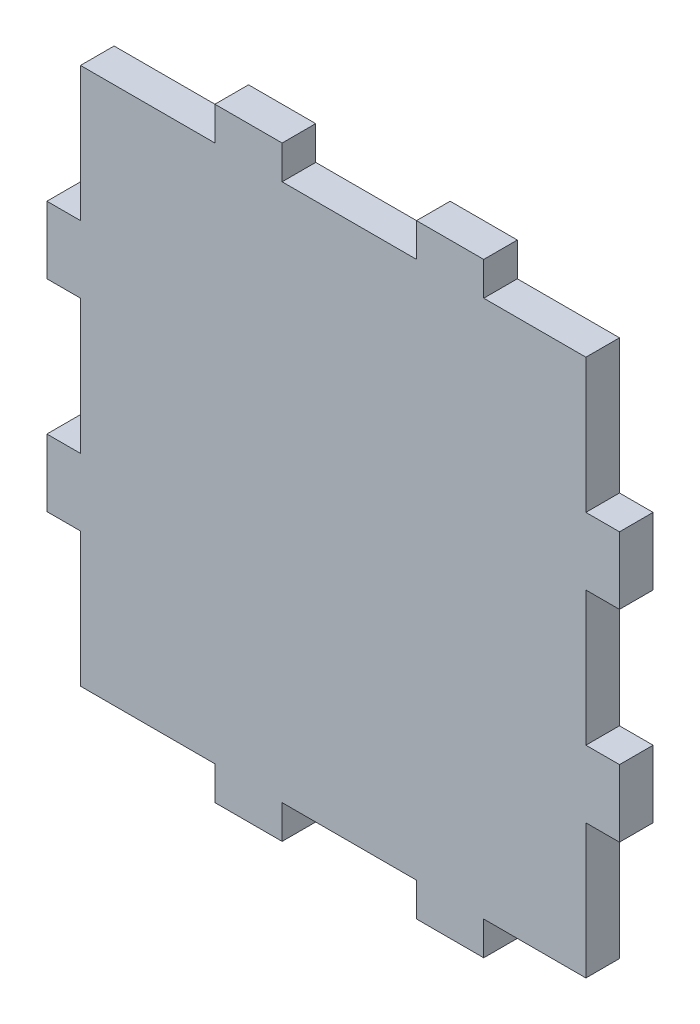
SolidWorks part; units mm, degrees
ref_plane "Front Plane" through (0, 0, 0) normal (0, 0, 1) x (1, 0, 0)
ref_plane "Top Plane" through (0, 0, 0) normal (0, 1, 0) x (1, 0, 0)
ref_plane "Right Plane" through (0, 0, 0) normal (1, 0, 0) x (0, 0, -1)
sketch "Sketch1" plane through (0, 0, 0) normal (0, 0, 1) x (1, 0, 0)
  line L0 (19.05, 0) -> (31.75, 0)
  line L1 (0, 0) -> (12.7, 0)
  line L2 (0, 0) -> (0, -12.7)
  line L3 (0, -50.8) -> (12.7, -50.8)
  line L4 (47.752, -19.05) -> (47.752, -31.75)
  line L6 (12.7, 0) -> (12.7, 3.175)
  line L7 (12.7, 3.175) -> (19.05, 3.175)
  line L8 (19.05, 0) -> (19.05, 3.175)
  line L9 (0, -19.05) -> (0, -31.75)
  line L10 (31.75, 0) -> (31.75, 3.175)
  line L11 (31.75, 3.175) -> (38.1, 3.175)
  line L12 (38.1, 0) -> (38.1, 3.175)
  line L13 (47.752, -12.7) -> (50.927, -12.7)
  line L14 (47.752, -38.1) -> (47.752, -50.8)
  line L15 (47.752, -19.05) -> (50.927, -19.05)
  line L16 (50.927, -12.7) -> (50.927, -19.05)
  line L17 (47.752, -31.75) -> (50.927, -31.75)
  line L18 (38.1, -50.8) -> (47.752, -50.8)
  line L19 (47.752, -38.1) -> (50.927, -38.1)
  line L20 (50.927, -31.75) -> (50.927, -38.1)
  line L21 (19.05, -50.8) -> (31.75, -50.8)
  line L22 (31.75, -50.8) -> (31.75, -53.975)
  line L23 (31.75, -53.975) -> (38.1, -53.975)
  line L24 (38.1, -50.8) -> (38.1, -53.975)
  line L25 (0, -38.1) -> (0, -50.8)
  line L26 (12.7, -50.8) -> (12.7, -53.975)
  line L27 (12.7, -53.975) -> (19.05, -53.975)
  line L28 (19.05, -50.8) -> (19.05, -53.975)
  line L29 (0, -38.1) -> (-3.175, -38.1)
  line L30 (38.1, 0) -> (47.752, 0)
  line L31 (0, -31.75) -> (-3.175, -31.75)
  line L32 (-3.175, -38.1) -> (-3.175, -31.75)
  line L33 (0, -19.05) -> (-3.175, -19.05)
  line L34 (47.752, 0) -> (47.752, -12.7)
  line L35 (0, -12.7) -> (-3.175, -12.7)
  line L36 (-3.175, -19.05) -> (-3.175, -12.7)
  dimension "D3" = 12.7
  dimension "D4" = 6.35
  dimension "D5" = 3.175
  dimension "D6" = 6.35
  dimension "D7" = 3.175
  dimension "D8" = 12.7
  dimension "D9" = 3.175
  dimension "D10" = 6.35
  dimension "D11" = 3.175
  dimension "D12" = 3.175
  dimension "D13" = 6.35
  dimension "D14" = 12.7
  dimension "D15" = 6.35
  dimension "D16" = 3.175
  dimension "D17" = 9.652
  dimension "D18" = 6.35
  dimension "D19" = 12.7
  dimension "D20" = 3.175
  dimension "D21" = 3.175
  dimension "D22" = 6.35
  dimension "D23" = 12.7
  dimension "D24" = 12.7
  dimension "D25" = 6.35
  dimension "D26" = 12.7
  dimension "D27" = 3.175
  dimension "D28" = 12.7
  dimension "D29" = 12.7
  dimension "D30" = 12.7
extrude "Boss-Extrude1" add sketch "Sketch1" along normal blind 3.175 contours L36 L33 L2 L31 L32 L29 L3 L26 L27 L28 L22 L23 L24 L4 L19 L20 L17 L15 L16 L13 L1 L12 L11 L10 L8 L7 L6 L35
